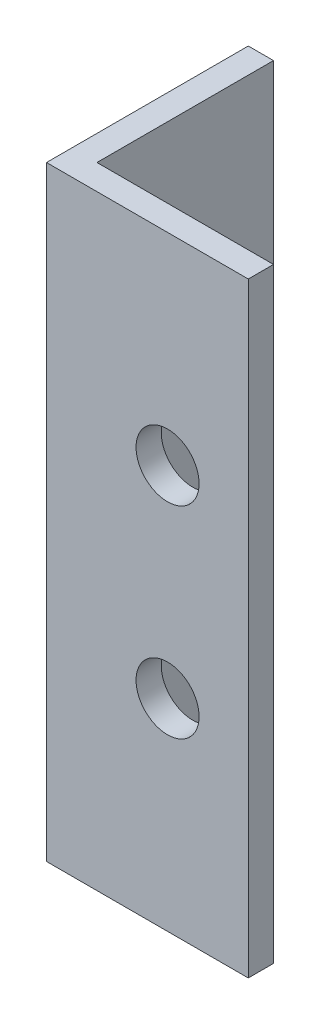
SolidWorks part; units mm, degrees
ref_plane "Front Plane" through (0, 0, 0) normal (0, 0, 1) x (1, 0, 0)
ref_plane "Top Plane" through (0, 0, 0) normal (0, 1, 0) x (1, 0, 0)
ref_plane "Right Plane" through (0, 0, 0) normal (1, 0, 0) x (0, 0, -1)
sketch "Sketch1" plane through (0, 0, 0) normal (0, 1, 0) x (1, 0, 0)
  line L0 (0, 0) -> (25.4, 0)
  line L1 (25.4, 0) -> (25.4, 3.175)
  line L2 (0, 0) -> (0, 25.4)
  line L3 (0, 25.4) -> (3.175, 25.4)
  line L4 (3.175, 25.4) -> (3.175, 3.175)
  line L5 (3.175, 3.175) -> (25.4, 3.175)
extrude "Boss-Extrude1" add sketch "Sketch1" along normal blind 76.2
sketch "Sketch2" plane through (0, 0, 0) normal (0, 0, 1) x (1, 0, 0)
  line L0 (0, 76.2) -> (25.4, 76.2) construction
  line L1 (0, 0) -> (25.4, 0) construction
  line L2 (25.4, 76.2) -> (25.4, 0) construction
  circle A0 centre (15.24, 25.4) radius 3.9688
  circle A1 centre (15.24, 50.8) radius 3.9688
  dimension "D1" = 25.4
  dimension "D3" = 10.16
  dimension "D4" = 10.16
  dimension "D2" = 25.4
extrude "Cut-Extrude1" cut sketch "Sketch2" against normal up to next
sketch "Sketch3" plane through (0, 0, 0) normal (0, 0, 1) x (1, 0, 0)
  point P0 (15.24, 25.4)
  point P1 (15.24, 50.8)
